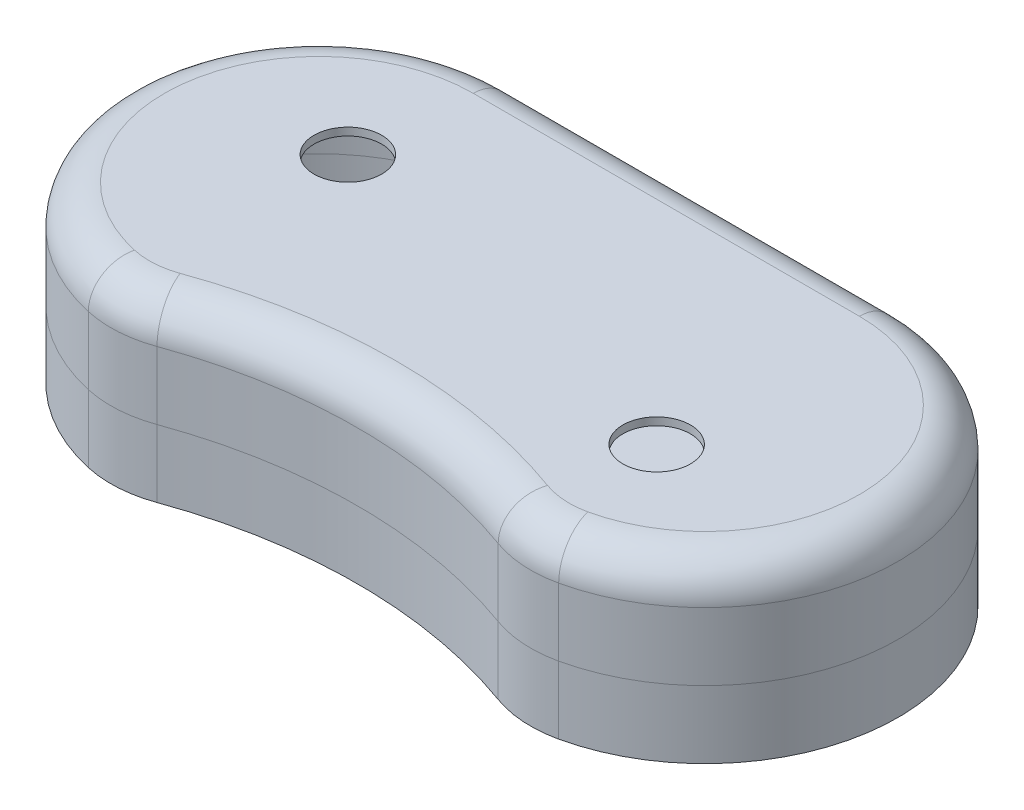
SolidWorks part; units mm, degrees
ref_plane "Front Plane" through (0, 0, 0) normal (0, 0, 1) x (1, 0, 0)
ref_plane "Top Plane" through (0, 0, 0) normal (0, 1, 0) x (1, 0, 0)
ref_plane "Right Plane" through (0, 0, 0) normal (1, 0, 0) x (0, 0, -1)
sketch "Sketch7" plane through (0, 0, 0) normal (0, 1, 0) x (1, 0, 0)
  line L1 (-25, -45) -> (25, -45)
  line L2 (-25, -45) -> (-25, 45)
  line L3 (-25, 45) -> (25, 45)
  line L4 (25, -45) -> (25, 45)
  line L5 (-25, -45) -> (25, 45) construction
  line L6 (-25, 45) -> (25, -45) construction
  arc A0 (25, 45) -> (25, -55) centre (25, -5) cw
  arc A1 (-25, -45) -> (25, -55) centre (-25, -175) cw
  point P0 (0, 0)
  dimension "D3" = 50
  dimension "D1" = 50
  dimension "D2" = 90
extrude "Boss-Extrude1" add sketch "Sketch7" along normal blind 45
fillet "Fillet2" radius 30 1 edges at (25, 22.5, 55)
mirror "Mirror1" about plane through (-25, 45, 45) normal (-1, 0, 0) of bodies 107
sketch "Sketch11" plane through (0, 45, 0) normal (0, 1, 0) x (1, 0, 0)
  line L0 (-25, -45) -> (-25, 45) construction
  line L3 (-75, 45) -> (25, 45) construction
sketch "Sketch10" plane through (0, 45, 0) normal (0, 1, 0) x (1, 0, 0)
  line L1 (-75, 45) -> (25, 45) construction
  line L3 (-77.487, 5) -> (-25, 5) construction
  line L4 (27.487, -20) -> (-25, -20) construction
  line L6 (-25, -45) -> (-25, 45) construction
  circle A0 centre (-77.487, 5) radius 8.75
  circle A1 centre (27.487, -20) radius 8.75
  dimension "D2" = 17.5
  dimension "D1" = 25
  dimension "D5" = 40
fillet "Fillet4" radius 10 6 edges at (-25, 45, 45) (-77.4623, 45, 54.4582) (-124.6981, 45, -0.4863) (-25, 45, -45) (74.6981, 45, -0.4863) (27.4623, 45, 54.4582)
shell "Shell1" thickness 2
extrude "Cut-Extrude1" cut sketch "Sketch10" against normal up to next
sketch "Sketch12" plane through (0, 45, 0) normal (0, 1, 0) x (1, 0, 0)
  circle A0 centre (-86.8434, -32.8202) radius 7.5
  circle A1 centre (33.8767, 19.895) radius 7.5
  dimension "D1" = 15
extrude "Boss-Extrude2" add sketch "Sketch12" against normal blind 25.7
sketch "Sketch13" plane through (0, 0, -45) normal (0, 0, -1) x (-1, 0, 0)
  line L0 (75, 35) -> (75, 0) construction
  line L1 (19, 22.5) -> (31, 22.5)
  line L2 (19, 22.5) -> (19, 12.5)
  line L3 (19, 12.5) -> (31, 12.5)
  line L4 (31, 22.5) -> (31, 12.5)
  line L5 (19, 22.5) -> (31, 12.5) construction
  line L6 (19, 12.5) -> (31, 22.5) construction
  line L7 (-25, 17.5) -> (75, 17.5) construction
  line L8 (-25, 35) -> (-25, 0) construction
  line L9 (25, 35) -> (25, 10) construction
  line L10 (75, 35) -> (-25, 35) construction
  point P0 (25, 17.5)
  point P11 (31, 17.5)
  point P18 (25, 22.5)
  dimension "D1" = 10
  dimension "D2" = 12
sketch "Sketch14" plane through (0, 0, -45) normal (0, 0, -1) x (-1, 0, 0)
  line L0 (-94.911, 17.5) -> (148.5543, 17.5)
  line L1 (-25, 35) -> (-25, 0) construction
sketch "Sketch29" plane through (0, 0, 0) normal (0, -1, 0) x (1, 0, 0)
  circle A0 centre (-86.8434, 32.8202) radius 7.5
  circle A1 centre (33.8767, -19.895) radius 7.5
extrude "Boss-Extrude5" add sketch "Sketch29" against normal blind 17.5
extrude "Cut-Extrude4" cut sketch "Sketch13" against normal up to next contours L2 L3 L4 L1
fillet "Fillet7" radius 2 4 edges at (-19, 12.5, -44) (-31, 12.5, -44) (-31, 22.5, -44) (-19, 22.5, -44)
sketch "Sketch16" plane through (0, 0, 0) normal (0, -1, 0) x (1, 0, 0)
  line L0 (71.9824, 3.1) -> (-121.9824, 3.1) construction
  line L1 (-25, 45) -> (-25, -45) construction
  line L2 (-75, -45) -> (25, -45) construction
  circle A0 centre (-46.4, -28.3) radius 3.5
  circle A4 centre (-46.4, 34.5) radius 3.5
  circle A6 centre (-3.6, -28.3) radius 3.5
  circle A7 centre (-3.6, 34.5) radius 3.5
  dimension "D3" = 7
  dimension "D1" = 62.8
  dimension "D2" = 42.8
  dimension "D4" = 48.1
hole_wizard "CBORE for M3 Pan Head Machine Screw3" [suppressed] positions "Sketch24" profile "Sketch25" counterbore size "M3" standard "ANSI Metric"
sketch "Sketch24" plane through (0, 0, 0) normal (0, -1, 0) x (-1, 0, 0)
  point P0 (-33.8767, 19.895)
  point P3 (86.8434, -32.8202)
sketch "Sketch25" plane through (33.8767, 0, -19.895) normal (1, 0, 0) x (0, 0, -1)
  line L0 (0, 0) -> (0, 31.0215)
  line L1 (0, 31.0215) -> (1.7, 30)
  line L2 (1.7, 30) -> (1.7, 15)
  line L3 (1.7, 15) -> (3.5, 15)
  line L5 (3.5, 15) -> (3.5, 0.025)
  line L6 (3.5, 0.025) -> (3.525, 0)
  line L7 (3.525, 0) -> (0, 0)
  line L8 (-3.5, 0.025) -> (-3.525, 0) construction
  line L10 (0, 31.0215) -> (-1.7, 30) construction
  line L11 (0, -6.35) -> (0, 107.95) construction
  dimension "Hole Dia." = 3.4
  dimension "Hole Depth" = 30
  dimension "C'Bore Dia." = 7
  dimension "C'Bore Depth" = 15
  dimension "Near C'Sink Dia." = 7.05
  dimension "Near C'Sink Angle" = 90
  dimension "Drill Angle" = 118
split "Split1" trim tools "Sketch14" bodies to split 117 resulting bodies 111 112
hole_wizard "Hole1" [suppressed] positions "Sketch26" profile "Sketch27" legacy
sketch "Sketch26" [suppressed] plane through (0, 22.5, 0) normal (0, -1, 0) x (-1, 0, 0)
  point P0 (-33.8767, 19.895)
  point P3 (86.8434, -32.8202)
sketch "Sketch27" plane through (33.8767, 22.5, -19.895) normal (1, 0, 0) x (0, 0, -1)
  line L0 (0, 0) -> (0, 10)
  line L1 (0, 10) -> (1.5, 10)
  line L2 (1.5, 10) -> (1.5, 2)
  line L3 (1.5, 2) -> (2.65, 2)
  line L4 (2.65, 2) -> (2.65, 0)
  line L5 (2.65, 0) -> (0, 0)
  line L6 (0, 110) -> (0, -10) construction
  dimension "Diameter" = 3
  dimension "Depth" = 10
  dimension "C-Bore Diameter" = 5.3
  dimension "C-Bore Depth" = 2
